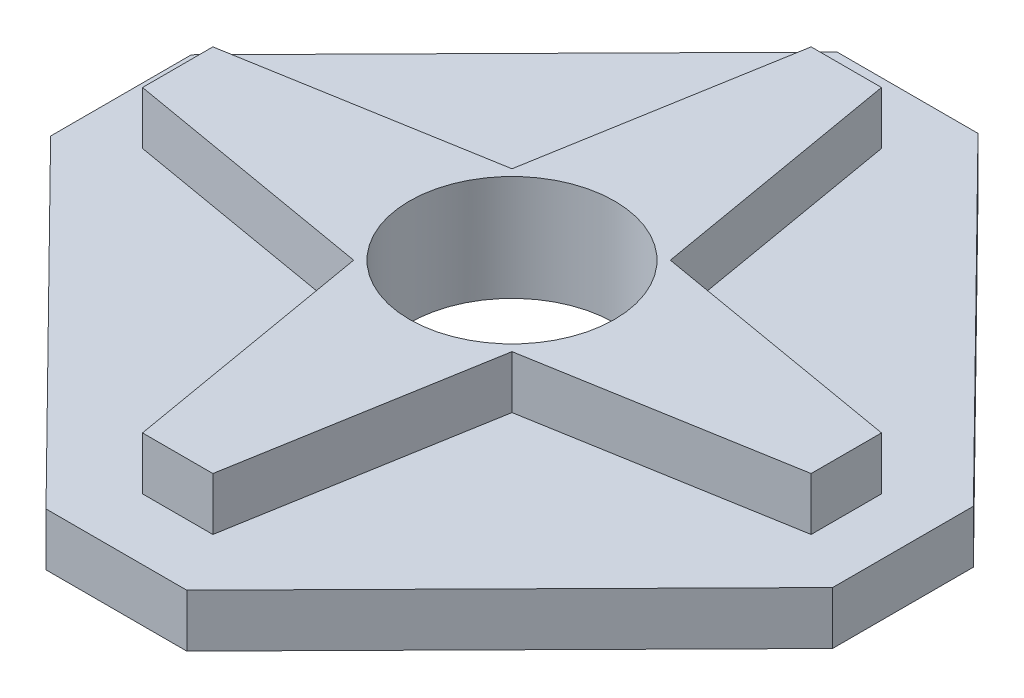
SolidWorks part; units mm, degrees
ref_plane "Front Plane" through (0, 0, 0) normal (0, 0, 1) x (1, 0, 0)
ref_plane "Top Plane" through (0, 0, 0) normal (0, 1, 0) x (1, 0, 0)
ref_plane "Right Plane" through (0, 0, 0) normal (1, 0, 0) x (0, 0, -1)
sketch "Sketch1" plane through (0, 0, 0) normal (0, 1, 0) x (1, 0, 0)
  line L0 (-2, 19) -> (2, 19)
  line L1 (2, 19) -> (4.5, 4.5)
  line L2 (4.5, 4.5) -> (19, 2)
  line L3 (19, 2) -> (19, -2)
  line L4 (0, 23.322) -> (0, -6.0031) construction
  line L5 (-19, 2) -> (-19, -2)
  line L6 (-4.5, 4.5) -> (-19, 2)
  line L7 (-2, 19) -> (-4.5, 4.5)
  line L8 (-21.0901, 0) -> (27.576, 0) construction
  line L9 (-2, -19) -> (-4.5, -4.5)
  line L10 (-4.5, -4.5) -> (-19, -2)
  line L11 (4.5, -4.5) -> (19, -2)
  line L12 (2, -19) -> (4.5, -4.5)
  line L13 (-2, -19) -> (2, -19)
  point P12 (0, 19)
  point P14 (0, -19)
  point P18 (-19, 0)
  point P19 (19, 0)
  dimension "D1" = 19
  dimension "D2" = 19
  dimension "D3" = 4.5
  dimension "D4" = 4.5
  dimension "D5" = 4
  dimension "D6" = 4
extrude "Boss-Extrude1" add sketch "Sketch1" along normal blind 3
sketch "Sketch2" plane through (0, 0, 0) normal (0, 1, 0) x (1, 0, 0)
  line L0 (4, 22.4839) -> (-4, 22.4839)
  line L5 (-4, 22.4839) -> (-22.222, 4)
  line L6 (-22.222, 4) -> (-22.222, -4)
  line L7 (0, 31.9727) -> (0, -21.7211) construction
  line L8 (22.222, 4) -> (22.222, -4)
  line L9 (4, 22.4839) -> (22.222, 4)
  line L10 (-33.0569, 0) -> (30.5836, 0) construction
  line L11 (4, -22.4839) -> (22.222, -4)
  line L12 (-4, -22.4839) -> (-22.222, -4)
  line L13 (4, -22.4839) -> (-4, -22.4839)
  point P10 (0, 22.4839)
  point P12 (0, -22.4839)
  point P15 (22.222, 0)
  point P16 (-22.222, 0)
  dimension "D1" = 4
  dimension "D2" = 4
  dimension "D3" = 0
  dimension "D4" = 0
extrude "Boss-Extrude2" add sketch "Sketch2" against normal blind 3
sketch "Sketch4" plane through (0, 0, 0) normal (0, 1, 0) x (1, 0, 0)
  circle A0 centre (0, 0) radius 5.8292
extrude "Cut-Extrude3" cut sketch "Sketch4" along normal mid plane 20
